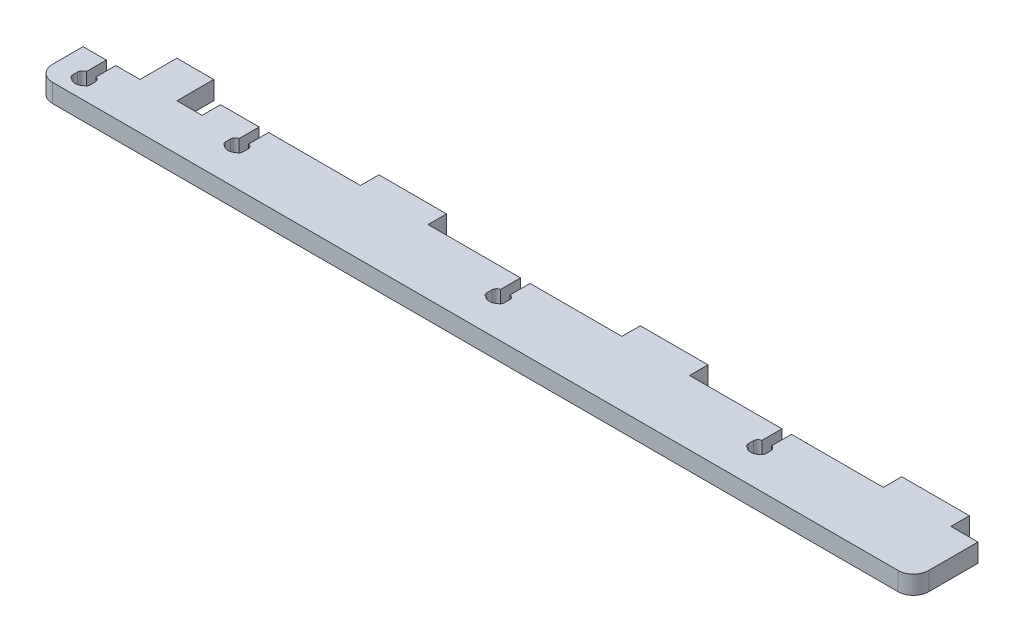
SolidWorks part; units mm, degrees
ref_plane "Alzado" through (0, 0, 0) normal (0, 0, 1) x (1, 0, 0)
ref_plane "Planta" through (0, 0, 0) normal (0, 1, 0) x (1, 0, 0)
ref_plane "Vista lateral" through (0, 0, 0) normal (1, 0, 0) x (0, 0, -1)
sketch "Croquis1" plane through (0, 0, 0) normal (0, 1, 0) x (1, 0, 0)
  line L0 (-113.4766, -5.7424) -> (-113.4766, -11.2465) construction
  line L1 (-122.4766, -5.7424) -> (-114.9266, -5.7424)
  line L2 (-122.4766, -5.7424) -> (-122.4766, -15.7424)
  line L3 (-117.4766, -20.7424) -> (157.5234, -20.7424)
  line L4 (162.5234, -0.7424) -> (162.5234, -15.7424)
  line L5 (-114.9266, -12.2426) -> (-114.9266, -5.7424)
  line L6 (-111.8266, -12.2426) -> (-111.8266, -5.7424)
  line L7 (-110.5363, -13.7707) -> (-110.5363, -15.3207)
  line L8 (-111.2451, -16.6226) -> (-111.4144, -16.6226)
  line L9 (-115.5081, -16.6226) -> (-115.3389, -16.6226)
  line L10 (-116.217, -13.7707) -> (-116.217, -15.3207)
  line L11 (-69.7766, 0.2576) -> (-69.7766, -5.2465) construction
  line L12 (-105.4766, -5.7424) -> (-104.4766, -5.7424)
  line L13 (131.2234, 0.2576) -> (101.8734, 0.2576)
  line L14 (-103.9766, 6.2576) -> (-91.9766, 6.2576)
  line L15 (46.2234, 0.2576) -> (16.8734, 0.2576)
  line L16 (-69.7766, 0.2576) -> (-69.7766, -5.2465) construction
  line L17 (162.5234, -0.7424) -> (162.5234, 0.2576)
  line L18 (162.5234, 0.2576) -> (154.2234, 0.2576)
  line L19 (-83.7766, -5.7424) -> (-83.7766, 0.2576)
  line L20 (-71.2266, -6.2426) -> (-71.2266, 0.2576)
  line L21 (-68.1266, -6.2426) -> (-68.1266, 0.2576)
  line L22 (-66.8363, -7.7707) -> (-66.8363, -9.3207)
  line L23 (-67.5451, -10.6226) -> (-67.7144, -10.6226)
  line L24 (-71.8081, -10.6226) -> (-71.6389, -10.6226)
  line L25 (-72.517, -7.7707) -> (-72.517, -9.3207)
  line L26 (46.7234, 6.2576) -> (68.7234, 6.2576)
  line L27 (-39.7766, 0.2576) -> (-38.7766, 0.2576)
  line L28 (-15.7766, 0.2576) -> (-14.7766, 0.2576)
  line L29 (-38.2766, 6.2576) -> (-16.2766, 6.2576)
  line L30 (-38.7766, 0.2576) -> (-68.1266, 0.2576)
  line L31 (-91.4766, -5.7424) -> (-90.4766, -5.7424)
  line L32 (-91.4766, -5.7424) -> (-83.7766, -5.7424)
  line L33 (13.7734, -6.2426) -> (13.7734, 0.2576)
  line L34 (16.8734, -6.2426) -> (16.8734, 0.2576)
  line L35 (18.1637, -7.7707) -> (18.1637, -9.3207)
  line L36 (17.4549, -10.6226) -> (17.2856, -10.6226)
  line L37 (13.1919, -10.6226) -> (13.3611, -10.6226)
  line L38 (12.483, -7.7707) -> (12.483, -9.3207)
  line L39 (15.2234, 0.2576) -> (15.2234, -5.2465) construction
  line L40 (15.2234, 0.2576) -> (15.2234, -5.2465) construction
  line L41 (131.7234, 6.2576) -> (153.7234, 6.2576)
  line L42 (-104.4766, -5.7424) -> (-103.9766, -5.7424)
  line L43 (-103.9766, 6.2576) -> (-103.9766, -5.7424)
  line L44 (98.7734, -6.2426) -> (98.7734, 0.2576)
  line L45 (101.8734, -6.2426) -> (101.8734, 0.2576)
  line L46 (103.1637, -7.7707) -> (103.1637, -9.3207)
  line L47 (102.4549, -10.6226) -> (102.2856, -10.6226)
  line L48 (98.1919, -10.6226) -> (98.3611, -10.6226)
  line L49 (97.483, -7.7707) -> (97.483, -9.3207)
  line L50 (100.2234, 0.2576) -> (100.2234, -5.2465) construction
  line L51 (100.2234, 0.2576) -> (100.2234, -5.2465) construction
  line L52 (-71.2266, 0.2576) -> (-83.7766, 0.2576)
  line L53 (-111.8266, -5.7424) -> (-104.4766, -5.7424)
  line L54 (13.7734, 0.2576) -> (-15.7766, 0.2576)
  line L55 (98.7734, 0.2576) -> (69.2234, 0.2576)
  line L56 (-91.9766, -5.7424) -> (-91.4766, -5.7424)
  line L58 (-38.7766, 0.2576) -> (-38.2766, 0.2576)
  line L59 (-16.2766, 0.2576) -> (-15.7766, 0.2576)
  line L60 (-16.2766, 0.2576) -> (-15.7766, 0.2576)
  line L61 (-104.4766, -5.7424) -> (-103.9766, -5.7424)
  line L62 (-91.9766, -5.7424) -> (-91.4766, -5.7424)
  line L64 (-91.9766, 6.2576) -> (-91.9766, -5.7424)
  line L65 (-38.7766, 0.2576) -> (-38.2766, 0.2576)
  line L66 (-38.2766, 6.2576) -> (-38.2766, 0.2576)
  line L67 (-16.2766, 6.2576) -> (-16.2766, 0.2576)
  line L68 (46.7234, 6.2576) -> (46.7234, 0.2576)
  line L69 (68.7234, 6.2576) -> (68.7234, 0.2576)
  line L70 (131.7234, 6.2576) -> (131.7234, 0.2576)
  line L71 (153.7234, 6.2576) -> (153.7234, 0.2576)
  line L72 (46.2234, 0.2576) -> (46.7234, 0.2576)
  line L73 (68.7234, 0.2576) -> (69.2234, 0.2576)
  line L74 (131.2234, 0.2576) -> (131.7234, 0.2576)
  line L75 (153.7234, 0.2576) -> (154.2234, 0.2576)
  arc A0 (-110.5363, -13.7707) -> (-111.8266, -12.2426) centre (-112.0863, -13.7707) ccw
  arc A1 (-111.2451, -16.6226) -> (-110.5363, -15.3207) centre (-112.0863, -15.3207) ccw
  arc A2 (-115.3389, -16.6226) -> (-111.4144, -16.6226) centre (-113.3766, -14.6611) ccw
  arc A3 (-115.5081, -16.6226) -> (-116.217, -15.3207) centre (-114.667, -15.3207) cw
  arc A4 (-116.217, -13.7707) -> (-114.9266, -12.2426) centre (-114.667, -13.7707) cw
  arc A5 (-66.8363, -7.7707) -> (-68.1266, -6.2426) centre (-68.3863, -7.7707) ccw
  arc A6 (-67.5451, -10.6226) -> (-66.8363, -9.3207) centre (-68.3863, -9.3207) ccw
  arc A7 (-71.6389, -10.6226) -> (-67.7144, -10.6226) centre (-69.6766, -8.6611) ccw
  arc A8 (-71.8081, -10.6226) -> (-72.517, -9.3207) centre (-70.967, -9.3207) cw
  arc A9 (-72.517, -7.7707) -> (-71.2266, -6.2426) centre (-70.967, -7.7707) cw
  arc A10 (18.1637, -7.7707) -> (16.8734, -6.2426) centre (16.6137, -7.7707) ccw
  arc A11 (17.4549, -10.6226) -> (18.1637, -9.3207) centre (16.6137, -9.3207) ccw
  arc A12 (13.3611, -10.6226) -> (17.2856, -10.6226) centre (15.3234, -8.6611) ccw
  arc A13 (13.1919, -10.6226) -> (12.483, -9.3207) centre (14.033, -9.3207) cw
  arc A14 (12.483, -7.7707) -> (13.7734, -6.2426) centre (14.033, -7.7707) cw
  arc A15 (103.1637, -7.7707) -> (101.8734, -6.2426) centre (101.6137, -7.7707) ccw
  arc A16 (102.4549, -10.6226) -> (103.1637, -9.3207) centre (101.6137, -9.3207) ccw
  arc A17 (98.3611, -10.6226) -> (102.2856, -10.6226) centre (100.3234, -8.6611) ccw
  arc A18 (98.1919, -10.6226) -> (97.483, -9.3207) centre (99.033, -9.3207) cw
  arc A19 (97.483, -7.7707) -> (98.7734, -6.2426) centre (99.033, -7.7707) cw
  arc A20 (162.5234, -15.7424) -> (157.5234, -20.7424) centre (157.5234, -15.7424) cw
  arc A21 (-122.4766, -15.7424) -> (-117.4766, -20.7424) centre (-117.4766, -15.7424) ccw
  point P6 (-113.4766, -5.7424)
  point P35 (-69.7766, 0.2576)
  point P109 (162.5234, -20.7424)
  point P112 (-122.4766, -20.7424)
  dimension "D15" = 5
  dimension "D1" = 285
  dimension "D3" = 9
  dimension "D7" = 6
  dimension "D13" = 3
  dimension "D16" = 15
  dimension "D21" = 3
extrude "Saliente-Extruir1" add sketch "Croquis1" along normal blind 6
